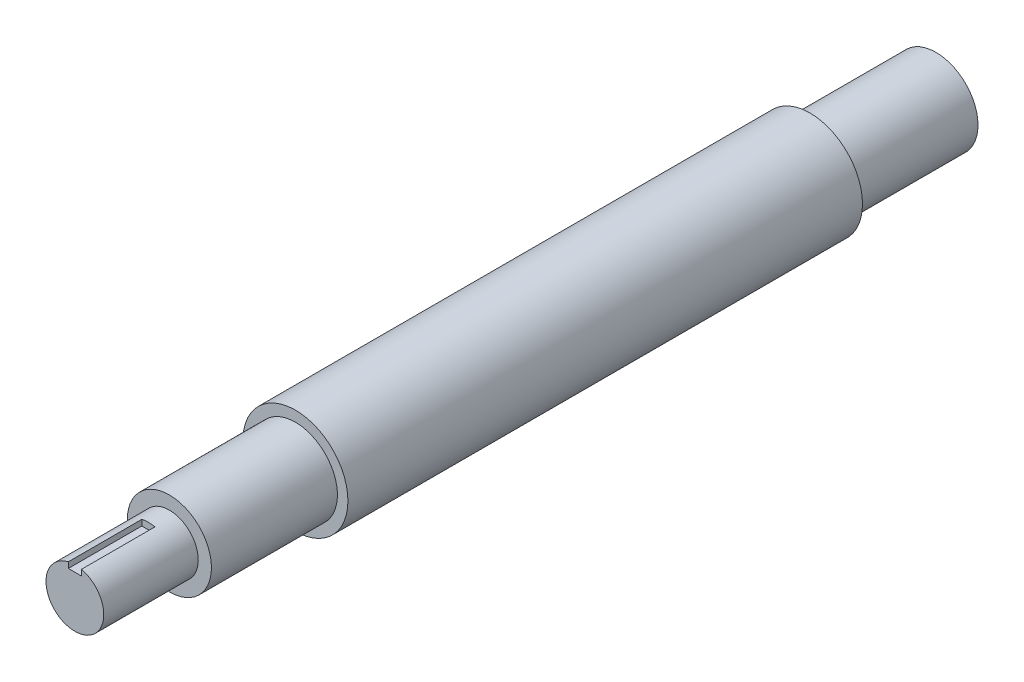
SolidWorks part; units mm, degrees
material "ASTM A36 Steel"
ref_plane "Front Plane" through (0, 0, 0) normal (0, 0, 1) x (1, 0, 0)
ref_plane "Top Plane" through (0, 0, 0) normal (0, 1, 0) x (1, 0, 0)
ref_plane "Right Plane" through (0, 0, 0) normal (1, 0, 0) x (0, 0, -1)
sketch "Sketch1" plane through (0, 0, 0) normal (0, 0, 1) x (1, 0, 0)
  line L0 (-105.6108, 0) -> (105.6108, 0) construction
  line L1 (0, -91.8487) -> (0, 91.8487) construction
  circle A0 centre (0, 0) radius 31.75
  point P4 (0, 0)
  point P8 (0, 0)
  dimension "D1" = 63.5
extrude "Boss-Extrude1" add sketch "Sketch1" along normal mid plane 311.15
sketch "Sketch2" plane through (0, 0, 155.575) normal (0, 0, 1) x (1, 0, 0)
  circle A0 centre (0, 0) radius 25.4
  dimension "D1" = 50.8
extrude "Boss-Extrude2" add sketch "Sketch2" along normal blind 76.2
sketch "Sketch3" plane through (0, 0, -155.575) normal (0, 0, -1) x (-1, 0, 0)
  circle A0 centre (0, 0) radius 25.4
  dimension "D1" = 50.8
extrude "Boss-Extrude3" add sketch "Sketch3" along normal blind 76.2
sketch "Sketch5" plane through (0, 0, -231.775) normal (0, 0, -1) x (-1, 0, 0)
  circle A0 centre (0, 0) radius 17.4625
  dimension "D1" = 34.925
extrude "Boss-Extrude5" [suppressed] add sketch "Sketch5" along normal blind 25.4
sketch "Sketch6" plane through (0, 0, 0) normal (1, 0, 0) x (0, 0, -1)
  line L0 (-255.2105, 0) -> (255.2105, 0) construction
  line L1 (0, -134.3892) -> (0, 134.3892) construction
  line L2 (-206.375, -104.8827) -> (-206.375, 104.8827) construction
  line L3 (206.375, -92.5613) -> (206.375, 92.5613) construction
  line L4 (-155.575, 31.75) -> (-155.575, -31.75) construction
  line L5 (155.575, -31.75) -> (155.575, 31.75) construction
  line L6 (149.225, -84.4665) -> (149.225, 84.4665) construction
  line L8 (-149.225, -69.4558) -> (-149.225, 69.4558) construction
  point P4 (0, 0)
  point P8 (0, 0)
  point P11 (-206.375, 0)
  point P14 (206.375, 0)
  point P21 (-149.225, 0)
  point P22 (149.225, 0)
  point P24 (149.225, 0)
  point P27 (-149.225, 0)
  dimension "D1" = 50.8
  dimension "D2" = 50.8
  dimension "D3" = 6.35
  dimension "D5" = 6.35
sketch "Sketch18" plane through (0, 0, 231.775) normal (0, 0, 1) x (1, 0, 0)
  circle A0 centre (0, 0) radius 17.4625
  dimension "D1" = 34.925
extrude "Boss-Extrude6" add sketch "Sketch18" along normal blind 57.15
sketch "Sketch20" plane through (0, 0, 288.925) normal (0, 0, 1) x (1, 0, 0)
  line L0 (-67.746, 0) -> (67.746, 0) construction
  line L1 (0, -47.1301) -> (0, 47.1301) construction
  line L3 (-3.9624, 13.5001) -> (3.9624, 13.5001)
  line L4 (-3.9624, 13.5001) -> (-3.9624, 21.4249)
  line L5 (-3.9624, 21.4249) -> (3.9624, 21.4249)
  line L6 (3.9624, 13.5001) -> (3.9624, 21.4249)
  line L7 (-3.9624, 13.5001) -> (3.9624, 21.4249) construction
  line L8 (-3.9624, 21.4249) -> (3.9624, 13.5001) construction
  circle A0 centre (0, 0) radius 17.4625 construction
  point P0 (0, 17.4625)
  point P5 (0, 0)
  point P9 (0, 0)
  dimension "D1" = 7.9248
  dimension "D2" = 7.9248
extrude "Cut-Extrude1" cut sketch "Sketch20" against normal blind 44.45
